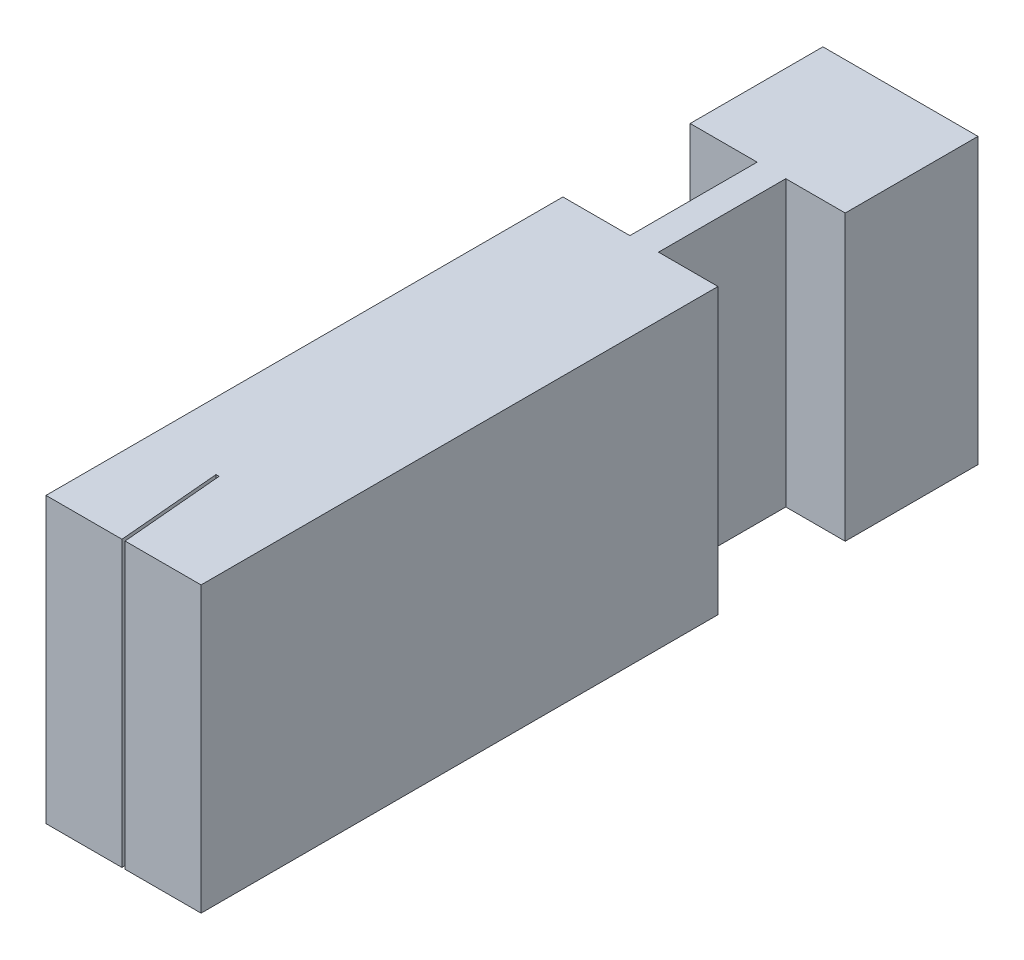
SolidWorks part; units mm, degrees
ref_plane "Front Plane" through (0, 0, 0) normal (0, 0, 1) x (1, 0, 0)
ref_plane "Top Plane" through (0, 0, 0) normal (0, 1, 0) x (1, 0, 0)
ref_plane "Right Plane" through (0, 0, 0) normal (1, 0, 0) x (0, 0, -1)
sketch "Sketch1" plane through (0, 0, 0) normal (0, 1, 0) x (1, 0, 0)
  line L16 (14.7, 0) -> (12.9569, 19.9239)
  line L22 (0, 0) -> (14.7, 0)
  line L26 (12.9569, 19.9239) -> (13.5569, 19.9239)
  line L27 (13.5569, 19.9239) -> (15.3, 0)
  line L28 (15.3, 0) -> (30, 0)
  line L37 (0, 100) -> (0, 0)
  line L38 (30, 100) -> (30, 0)
  line L39 (0, 100) -> (12.9569, 100)
  line L47 (18.5013, 100) -> (30, 100)
  line L48 (12.9569, 100) -> (12.9569, 124.6161)
  line L49 (12.9569, 124.6161) -> (0, 124.6161)
  line L50 (0, 124.6161) -> (0, 150.3028)
  line L51 (0, 150.3028) -> (30, 150.3028)
  line L52 (30, 150.3028) -> (30, 124.6161)
  line L53 (30, 124.6161) -> (18.5013, 124.6161)
  line L54 (18.5013, 124.6161) -> (18.5013, 100)
  point P15 (0, 0)
  point P20 (30, 113.2774)
  dimension "D1" = 100
  dimension "D2" = 30
  dimension "D3" = 0.6
  dimension "D4" = 95
  dimension "D5" = 20
extrude "Boss-Extrude1" add sketch "Sketch1" along normal blind 55
